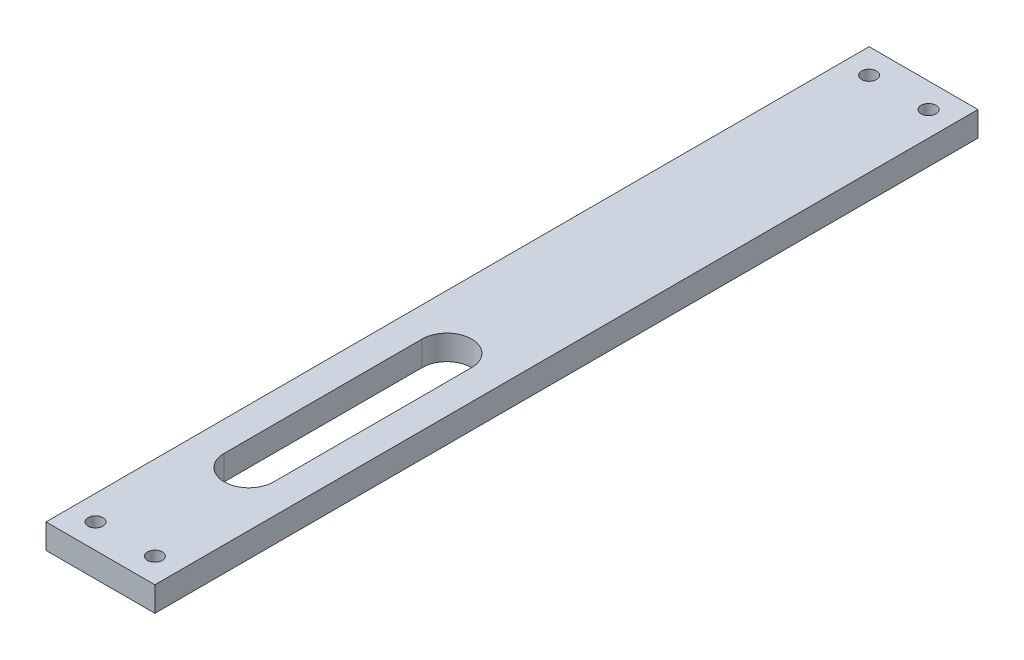
SolidWorks part; units mm, degrees
ref_plane "Front" through (0, 0, 0) normal (0, 0, 1) x (1, 0, 0)
ref_plane "Top" through (0, 0, 0) normal (0, 1, 0) x (1, 0, 0)
ref_plane "Right" through (0, 0, 0) normal (1, 0, 0) x (0, 0, -1)
sketch "Sketch1" plane through (0, 0, 0) normal (0, 1, 0) x (1, 0, 0)
  line L0 (11, 166.3) -> (11, 161.3)
  line L1 (0, 0) -> (22, 0)
  line L2 (0, 0) -> (0, 166.3)
  line L3 (0, 166.3) -> (22, 166.3)
  line L4 (22, 0) -> (22, 166.3)
  line L5 (5, 161.3) -> (17, 161.3)
  line L6 (0, 83.15) -> (22, 83.15)
  circle A0 centre (5, 161.3) radius 1.5
  circle A1 centre (17, 161.3) radius 1.5
  circle A2 centre (17, 5) radius 1.5
  circle A3 centre (5, 5) radius 1.5
  point P10 (11, 161.3)
  dimension "D1" = 166.3
  dimension "D2" = 22
  dimension "D3" = 12
extrude "Boss-Extrude1" add sketch "Sketch1" along normal blind 5
sketch "Sketch2" plane through (0, 0, 0) normal (0, -1, 0) x (-1, 0, 0)
  line L0 (-11, 0) -> (-11, 30)
  line L1 (0, 0) -> (-22, 0) construction
  line L2 (-11, 30) -> (-11, 70)
  line L3 (-11, 30) -> (-11, 70) construction
  line L4 (-16, 30) -> (-16, 70)
  line L5 (-6, 30) -> (-6, 70)
  arc A0 (-16, 30) -> (-6, 30) centre (-11, 30) ccw
  arc A1 (-6, 70) -> (-16, 70) centre (-11, 70) ccw
  point P5 (-11, 50)
  dimension "D3" = 5
  dimension "D1" = 30
  dimension "D2" = 40
extrude "Cut-Extrude1" cut sketch "Sketch2" against normal blind 5
